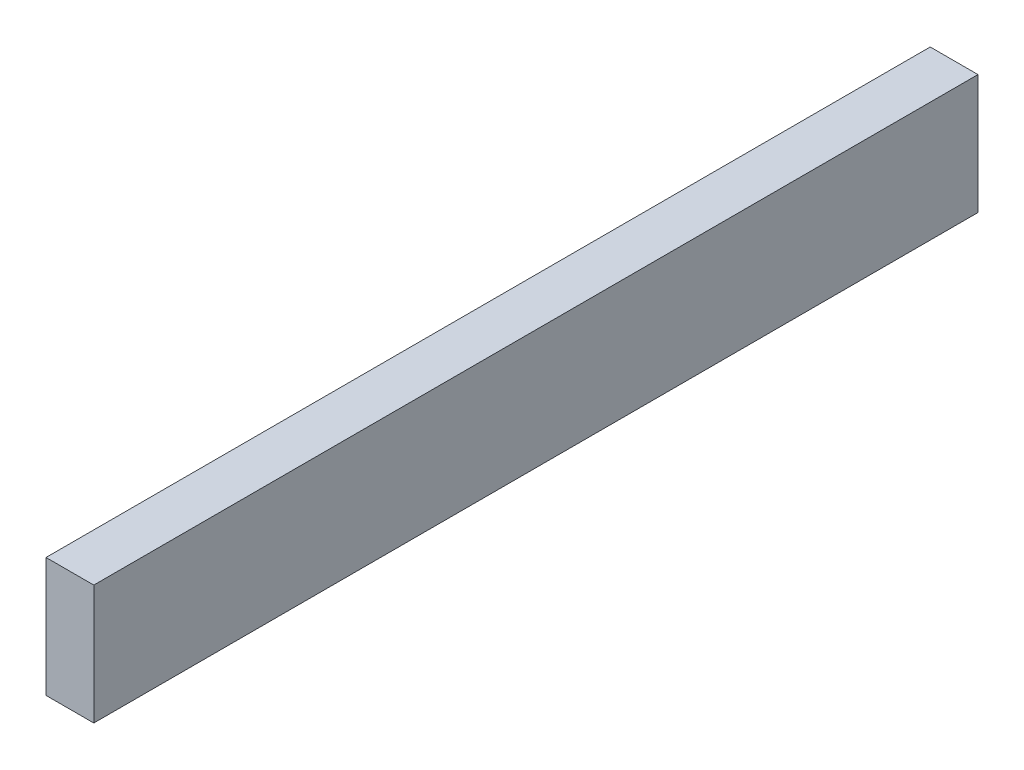
SolidWorks part; units mm, degrees
ref_plane "Front Plane" through (0, 0, 0) normal (0, 0, 1) x (1, 0, 0)
ref_plane "Top Plane" through (0, 0, 0) normal (0, 1, 0) x (1, 0, 0)
ref_plane "Right Plane" through (0, 0, 0) normal (1, 0, 0) x (0, 0, -1)
sketch "Sketch2" plane through (0, 0, 0) normal (1, 0, 0) x (0, 0, -1)
  line L1 (0, 0) -> (185, 0)
  line L2 (0, 0) -> (0, 25)
  line L3 (0, 25) -> (185, 25)
  line L4 (185, 0) -> (185, 25)
extrude "Boss-Extrude1" add sketch "Sketch2" along normal blind 10
